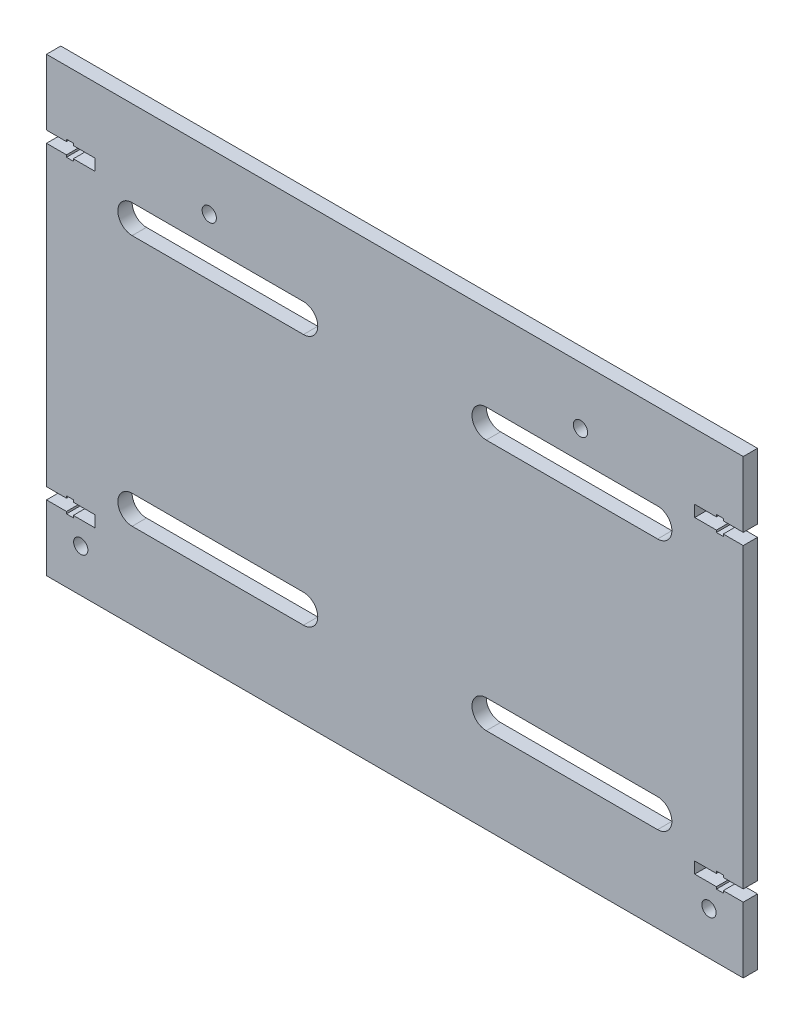
SolidWorks part; units mm, degrees
ref_plane "Front Plane" through (0, 0, 0) normal (0, 0, 1) x (1, 0, 0)
ref_plane "Top Plane" through (0, 0, 0) normal (0, 1, 0) x (1, 0, 0)
ref_plane "Right Plane" through (0, 0, 0) normal (1, 0, 0) x (0, 0, -1)
sketch "Sketch1" plane through (0, 0, 0) normal (0, 0, 1) x (1, 0, 0)
  line L1 (-107.2, 68.15) -> (136.8, 68.15)
  line L2 (-107.2, 68.15) -> (-107.2, -90)
  line L3 (-107.2, -90) -> (136.8, -90)
  line L4 (136.8, 68.15) -> (136.8, -90)
  dimension "D1" = 244
  dimension "D2" = 158.15
extrude "Boss-Extrude1" add sketch "Sketch1" along normal blind 5
sketch "Sketch2" plane through (0, 0, 0) normal (0, 0, -1) x (-1, 0, 0)
  line L0 (-136.8, 45.15) -> (-129.8, 45.15)
  line L1 (-136.8, -90) -> (-136.8, 68.15) construction
  line L2 (-119.8, 45.15) -> (-119.8, 41.15)
  line L3 (-119.8, 41.15) -> (-127.4, 41.15)
  line L4 (-136.8, 41.15) -> (-136.8, 45.15)
  line L5 (-136.8, -10.925) -> (-22.5815, -10.925) construction
  line L6 (-14.8, 68.15) -> (-14.8, -104.887) construction
  line L7 (-136.8, 68.15) -> (107.2, 68.15) construction
  line L8 (-145.5887, 43.15) -> (-78.8198, 43.15) construction
  line L9 (-129.8, 45.15) -> (-129.8, 45.9)
  line L10 (-129.8, 45.9) -> (-127.4, 45.9)
  line L11 (-127.4, 45.9) -> (-127.4, 45.15)
  line L12 (-127.4, 41.15) -> (-127.4, 40.4)
  line L13 (-127.4, 40.4) -> (-129.8, 40.4)
  line L14 (-129.8, 40.4) -> (-129.8, 41.15)
  line L15 (-127.4, 45.15) -> (-119.8, 45.15)
  line L16 (-129.8, 41.15) -> (-136.8, 41.15)
  line L17 (-129.8, -63) -> (-136.8, -63)
  line L18 (-127.4, -67) -> (-119.8, -67)
  line L19 (-129.8, -62.25) -> (-129.8, -63)
  line L20 (-127.4, -62.25) -> (-129.8, -62.25)
  line L21 (-127.4, -63) -> (-127.4, -62.25)
  line L22 (-127.4, -67.75) -> (-127.4, -67)
  line L23 (-129.8, -67.75) -> (-127.4, -67.75)
  line L24 (-129.8, -67) -> (-129.8, -67.75)
  line L25 (-136.8, -63) -> (-136.8, -67)
  line L26 (-119.8, -63) -> (-127.4, -63)
  line L27 (-119.8, -67) -> (-119.8, -63)
  line L28 (-136.8, -67) -> (-129.8, -67)
  line L29 (100.2, 41.15) -> (107.2, 41.15)
  line L30 (97.8, 45.15) -> (90.2, 45.15)
  line L31 (100.2, 40.4) -> (100.2, 41.15)
  line L32 (97.8, 40.4) -> (100.2, 40.4)
  line L33 (97.8, 41.15) -> (97.8, 40.4)
  line L34 (97.8, 45.9) -> (97.8, 45.15)
  line L35 (100.2, 45.9) -> (97.8, 45.9)
  line L36 (100.2, 45.15) -> (100.2, 45.9)
  line L37 (107.2, 41.15) -> (107.2, 45.15)
  line L38 (90.2, 41.15) -> (97.8, 41.15)
  line L39 (90.2, 45.15) -> (90.2, 41.15)
  line L40 (107.2, 45.15) -> (100.2, 45.15)
  line L41 (107.2, -67) -> (100.2, -67)
  line L42 (90.2, -67) -> (90.2, -63)
  line L43 (90.2, -63) -> (97.8, -63)
  line L44 (107.2, -63) -> (107.2, -67)
  line L45 (100.2, -67) -> (100.2, -67.75)
  line L46 (100.2, -67.75) -> (97.8, -67.75)
  line L47 (97.8, -67.75) -> (97.8, -67)
  line L48 (97.8, -63) -> (97.8, -62.25)
  line L49 (97.8, -62.25) -> (100.2, -62.25)
  line L50 (100.2, -62.25) -> (100.2, -63)
  line L51 (97.8, -67) -> (90.2, -67)
  line L52 (100.2, -63) -> (107.2, -63)
  dimension "D1" = 2
  dimension "D2" = 25
  dimension "D3" = 2
  dimension "D4" = 17
  dimension "D5" = 2.4
  dimension "D6" = 0.75
  dimension "D7" = 2.4
  dimension "D8" = 0.75
  dimension "D9" = 7
extrude "Cut-Extrude1" cut sketch "Sketch2" against normal blind 10
sketch "Sketch3" plane through (0, 0, 0) normal (0, 0, -1) x (-1, 0, 0)
  line L0 (-106.8, 38.15) -> (-46.8, 38.15)
  line L2 (-46.8, 28.15) -> (-106.8, 28.15)
  line L4 (-136.8, 68.15) -> (107.2, 68.15) construction
  line L5 (-136.8, -63) -> (-136.8, 41.15) construction
  line L6 (-14.8, 68.15) -> (-14.8, -90) construction
  line L7 (107.2, -90) -> (-136.8, -90) construction
  line L8 (-136.8, -10.925) -> (110.571, -10.925) construction
  line L9 (-46.8, -50) -> (-106.8, -50)
  line L10 (-106.8, -60) -> (-46.8, -60)
  line L11 (77.2, -60) -> (17.2, -60)
  line L12 (17.2, -50) -> (77.2, -50)
  line L13 (17.2, 28.15) -> (77.2, 28.15)
  line L14 (77.2, 38.15) -> (17.2, 38.15)
  arc A0 (-106.8, 38.15) -> (-106.8, 28.15) centre (-106.8, 33.15) ccw
  arc A1 (-46.8, 28.15) -> (-46.8, 38.15) centre (-46.8, 33.15) ccw
  arc A2 (-46.8, -50) -> (-46.8, -60) centre (-46.8, -55) cw
  arc A3 (-106.8, -60) -> (-106.8, -50) centre (-106.8, -55) cw
  arc A4 (17.2, -50) -> (17.2, -60) centre (17.2, -55) ccw
  arc A5 (77.2, -60) -> (77.2, -50) centre (77.2, -55) ccw
  arc A6 (17.2, 28.15) -> (17.2, 38.15) centre (17.2, 33.15) cw
  arc A7 (77.2, 38.15) -> (77.2, 28.15) centre (77.2, 33.15) cw
  dimension "D3" = 30
  dimension "D1" = 30
  dimension "D2" = 10
  dimension "D4" = 60
extrude "Cut-Extrude2" cut sketch "Sketch3" against normal blind 10
sketch "Sketch4" plane through (0, 0, 0) normal (0, 0, -1) x (-1, 0, 0)
  line L0 (-136.8, 68.15) -> (107.2, 68.15) construction
  line L1 (-136.8, -63) -> (-136.8, 41.15) construction
  line L2 (-136.8, -90) -> (-136.8, -67) construction
  line L3 (107.2, -90) -> (-136.8, -90) construction
  circle A1 centre (50.2, 48.15) radius 2.5
  circle A3 centre (-79.8, 48.15) radius 2.5
  circle A7 centre (-124.8, -75.0046) radius 2.5
  circle A9 centre (95.2, -75.0046) radius 2.5
  dimension "D1" = 5
  dimension "D2" = 5
  dimension "D3" = 5
  dimension "D4" = 5
  dimension "D9" = 14.9954
  dimension "D5" = 20
  dimension "D6" = 57
  dimension "D7" = 130
  dimension "D8" = 12
  dimension "D10" = 220
extrude "Cut-Extrude3" cut sketch "Sketch4" against normal blind 10
